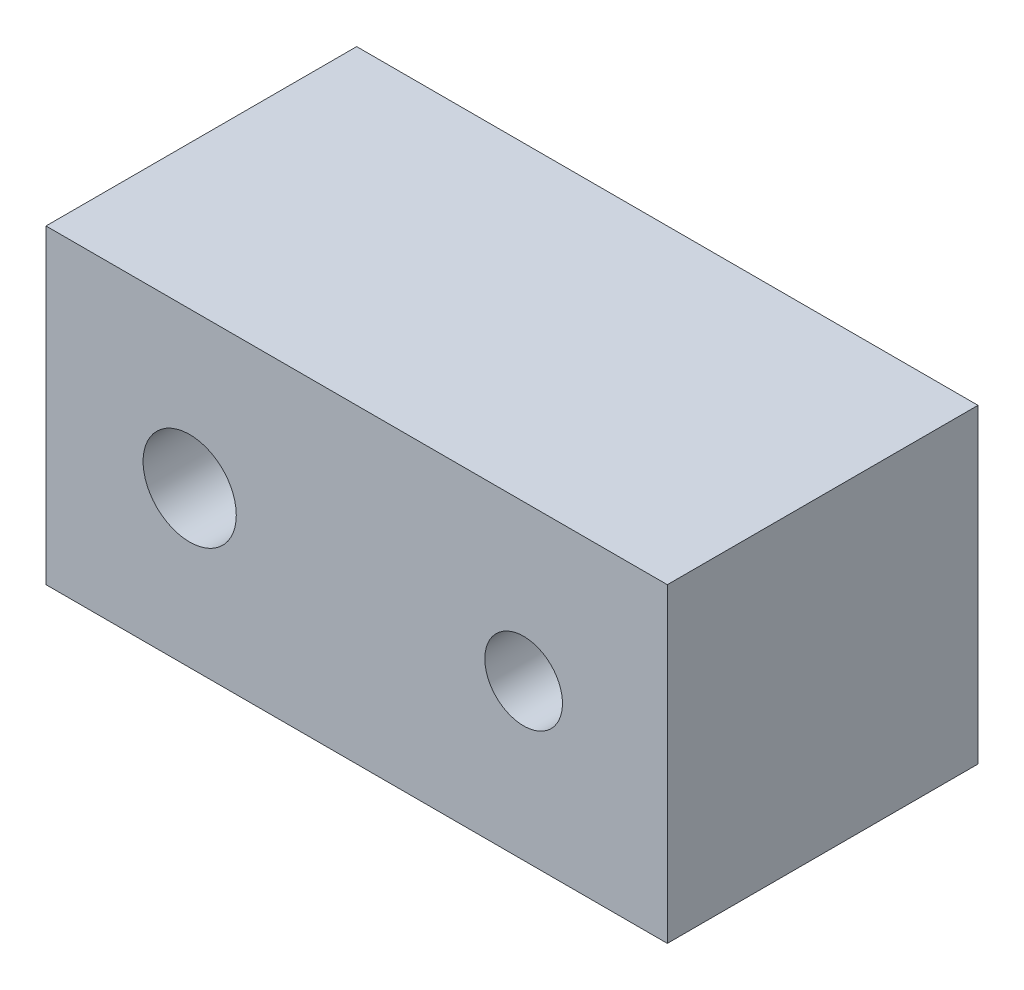
SolidWorks part; units mm, degrees
material "6061 合金"
ref_plane "前视基准面" through (0, 0, 0) normal (0, 0, 1) x (1, 0, 0)
ref_plane "上视基准面" through (0, 0, 0) normal (0, 1, 0) x (1, 0, 0)
ref_plane "右视基准面" through (0, 0, 0) normal (1, 0, 0) x (0, 0, -1)
sketch "草图1" plane through (0, 0, 0) normal (0, 0, 1) x (1, 0, 0)
  line L1 (-20, 10) -> (20, 10)
  line L2 (-20, 10) -> (-20, -10)
  line L3 (-20, -10) -> (20, -10)
  line L4 (20, 10) -> (20, -10)
  line L5 (-20, 10) -> (20, -10) construction
  line L6 (-20, -10) -> (20, 10) construction
  point P0 (0, 0)
  dimension "D1" = 40
  dimension "D2" = 20
extrude "凸台-拉伸1" add sketch "草图1" along normal blind 20
hole_wizard "M6 螺纹孔1" positions "3D草图1" profile "草图2" tap size "M6" standard "GB" end condition through all
sketch3d "3D草图1"
  line L0 (0, 0, 0) -> (-10.75, 0, 0) construction
  line L2 (0, 0, 0) -> (10.75, 0, 0) construction
  point P4 (10.75, 0, 0)
  point P17 (0, 0, 0)
  dimension "D1" = 10.75
  dimension "D2" = 10.75
sketch "草图2" plane through (10.75, 0, 0) normal (1, 0, 0) x (0, 1, 0)
  line L0 (0, 0) -> (0, 20)
  line L1 (0, 20) -> (2.5, 20)
  line L2 (2.5, 20) -> (2.5, 0.525)
  line L3 (2.5, 0.525) -> (3.025, 0)
  line L5 (3.025, 0) -> (0, 0)
  line L6 (-2.5, 0.525) -> (-3.025, 0) construction
  line L11 (0, -6.35) -> (0, 107.95) construction
  dimension "通孔螺纹孔钻头直径" = 5
  dimension "通孔螺纹孔钻头深度" = 20
  dimension "近端锥形沉头孔直径" = 6.05
  dimension "近端锥形沉头孔角度" = 90
cosmetic thread "孔螺蚊线1" parameters "D2"=6
sketch "草图3" plane through (0, 0, 20) normal (0, 0, 1) x (1, 0, 0)
  line L0 (-10.75, 0) -> (0, 0) construction
  circle A0 centre (-10.75, 0) radius 3
  dimension "D1" = 6
  dimension "D2" = 10.75
extrude "切除-拉伸1" cut sketch "草图3" against normal through all
